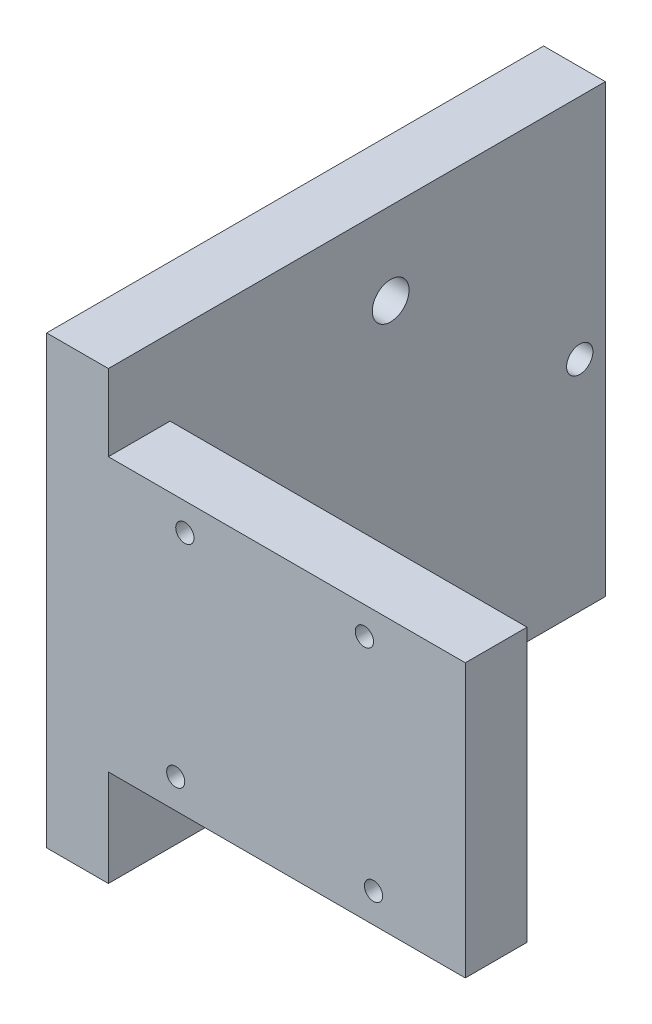
SolidWorks part; units mm, degrees
ref_plane "Front Plane" through (0, 0, 0) normal (0, 0, 1) x (1, 0, 0)
ref_plane "Top Plane" through (0, 0, 0) normal (0, 1, 0) x (1, 0, 0)
ref_plane "Right Plane" through (0, 0, 0) normal (1, 0, 0) x (0, 0, -1)
sketch "Sketch2" plane through (0, 0, 0) normal (0, 1, 0) x (1, 0, 0)
  line L0 (0, 0) -> (0, -21.4688)
  line L1 (0, -21.4688) -> (17.606, -21.4688)
extrude "Extrude-Thin1" add sketch "Sketch2" along normal blind 22 thin
sketch "Sketch4" plane through (0, 0, 0) normal (1, 0, 0) x (0, 0, -1)
  line L1 (-8.0712, 3.6786) -> (-13.1075, 3.6786)
  line L2 (-8.0712, 3.6786) -> (-8.0712, -1.7922)
  line L3 (-8.0712, -1.7922) -> (-13.1075, -1.7922)
  line L4 (-13.1075, 3.6786) -> (-13.1075, -1.7922)
  circle A0 centre (-1.2615, 10.7717) radius 0.6491
  circle A1 centre (-20.011, 10.7717) radius 0.6523
  circle A2 centre (-10.5893, 17.9382) radius 0.907
extrude "Cut-Extrude2" cut sketch "Sketch4" against normal through all
sketch "Sketch8" plane through (0, 0, 0) normal (0, 0, 1) x (1, 0, 0)
  circle A0 centre (3.7727, 16.8682) radius 0.4508
  circle A1 centre (12.6281, 16.8682) radius 0.4508
  circle A2 centre (13.0789, 6.2236) radius 0.4497
  circle A3 centre (3.3219, 6.2236) radius 0.4459
extrude "Cut-Extrude5" cut sketch "Sketch8" along normal through all
sketch "Sketch9" plane through (0, 0, 0) normal (0, 0, 1) x (1, 0, 0)
  line L0 (17.606, 22) -> (17.606, 0) construction
  line L1 (0, 22) -> (17.606, 22)
  line L2 (0, 22) -> (0, 18.2329)
  line L3 (0, 18.2329) -> (17.606, 18.2329)
  line L4 (17.606, 22) -> (17.606, 18.2329)
  line L6 (0, 0) -> (17.606, 0)
  line L7 (0, 0) -> (0, 4.7679)
  line L8 (0, 4.7679) -> (17.606, 4.7679)
  line L9 (17.606, 0) -> (17.606, 4.7679)
extrude "Cut-Extrude6" cut sketch "Sketch9" along normal through all
